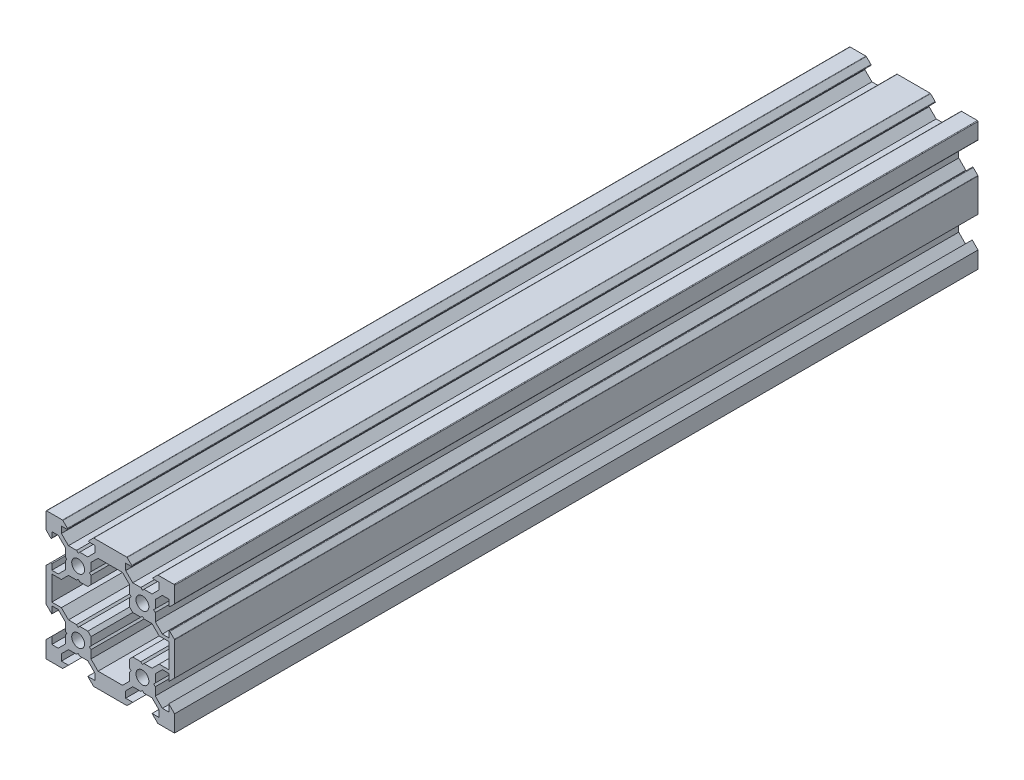
SolidWorks part; units mm, degrees
ref_plane "Front Plane" through (0, 0, 0) normal (0, 0, 1) x (1, 0, 0)
ref_plane "Top Plane" through (0, 0, 0) normal (0, 1, 0) x (1, 0, 0)
ref_plane "Right Plane" through (0, 0, 0) normal (1, 0, 0) x (0, 0, -1)
sketch "Sketch2" plane through (0, 0, 0) normal (0, 0, 1) x (1, 0, 0)
  line L160 (-6.22, 13.1326) -> (-4.02, 15.3326)
  line L161 (-4.02, 15.3326) -> (3.58, 15.3326)
  line L162 (3.58, 15.3326) -> (5.78, 13.1326)
  line L163 (5.78, 13.1326) -> (5.78, 10.6226)
  line L164 (5.78, 10.6226) -> (6.28, 10.1226)
  line L165 (6.28, 10.1226) -> (5.78, 9.6226)
  line L166 (5.78, 9.6226) -> (5.78, 7.1125)
  line L167 (5.78, 7.1125) -> (6.77, 6.1226)
  line L168 (6.77, 6.1226) -> (9.28, 6.1226)
  line L169 (9.28, 6.1226) -> (9.78, 6.6226)
  line L170 (9.78, 6.6226) -> (10.28, 6.1226)
  line L171 (10.28, 6.1226) -> (12.7901, 6.1226)
  line L172 (12.7901, 6.1226) -> (14.9901, 3.9226)
  line L173 (14.9901, 3.9226) -> (17.98, 3.9226)
  line L174 (17.98, 3.9226) -> (17.98, -3.6774)
  line L175 (17.98, -3.6774) -> (14.9901, -3.6774)
  line L176 (14.9901, -3.6774) -> (12.7901, -5.8774)
  line L177 (12.7901, -5.8774) -> (10.28, -5.8774)
  line L178 (9.78, -6.3774) -> (10.28, -5.8774)
  line L179 (9.28, -5.8774) -> (9.78, -6.3774)
  line L180 (9.28, -5.8774) -> (6.77, -5.8774)
  line L181 (6.77, -5.8774) -> (5.78, -6.8674)
  line L182 (5.78, -6.8674) -> (5.78, -9.3774)
  line L183 (6.28, -9.8774) -> (5.78, -9.3774)
  line L184 (5.78, -10.3774) -> (6.28, -9.8774)
  line L185 (5.78, -10.3774) -> (5.78, -12.8875)
  line L186 (5.78, -12.8875) -> (3.58, -15.0875)
  line L187 (3.58, -15.0875) -> (-4.02, -15.0875)
  line L188 (-4.02, -15.0875) -> (-6.22, -12.8875)
  line L189 (-6.22, -12.8875) -> (-6.22, -10.3774)
  line L190 (-6.72, -9.8774) -> (-6.22, -10.3774)
  line L191 (-6.22, -9.3774) -> (-6.72, -9.8774)
  line L192 (-6.22, -9.3774) -> (-6.22, -6.8674)
  line L193 (-6.22, -6.8674) -> (-7.2099, -5.8774)
  line L194 (-7.2099, -5.8774) -> (-9.72, -5.8774)
  line L195 (-10.22, -6.3774) -> (-9.72, -5.8774)
  line L196 (-10.72, -5.8774) -> (-10.22, -6.3774)
  line L197 (-10.72, -5.8774) -> (-13.23, -5.8774)
  line L198 (-13.23, -5.8774) -> (-15.43, -3.6774)
  line L199 (-15.43, -3.6774) -> (-18.42, -3.6774)
  line L200 (-18.42, -3.6774) -> (-18.42, 3.9226)
  line L201 (-18.42, 3.9226) -> (-15.43, 3.9226)
  line L202 (-15.43, 3.9226) -> (-13.23, 6.1226)
  line L203 (-13.23, 6.1226) -> (-10.72, 6.1226)
  line L204 (-10.72, 6.1226) -> (-10.22, 6.6226)
  line L205 (-10.22, 6.6226) -> (-9.72, 6.1226)
  line L206 (-9.72, 6.1226) -> (-7.2099, 6.1226)
  line L207 (-7.2099, 6.1226) -> (-6.22, 7.1125)
  line L208 (-6.22, 9.6226) -> (-6.72, 10.1226)
  line L209 (-6.72, 10.1226) -> (-6.22, 10.6226)
  line L210 (-6.22, 7.1125) -> (-6.22, 9.6226)
  line L211 (-6.22, 10.6226) -> (-6.22, 13.1326)
  line L212 (-5.0099, -16.0774) -> (-5.0099, -18.0774)
  line L213 (-5.0099, -18.0774) -> (-7.22, -18.0774)
  line L214 (-7.22, -18.0774) -> (-5.42, -19.8774)
  line L215 (-5.42, -19.8774) -> (4.98, -19.8774)
  line L216 (4.98, -19.8774) -> (6.78, -18.0774)
  line L217 (6.78, -18.0774) -> (4.57, -18.0774)
  line L218 (4.57, -18.0774) -> (4.57, -16.0774)
  line L219 (4.57, -16.0774) -> (6.77, -13.8774)
  line L220 (6.77, -13.8774) -> (9.28, -13.8774)
  line L221 (9.28, -13.8774) -> (9.78, -13.3774)
  line L222 (9.78, -13.3774) -> (10.28, -13.8774)
  line L223 (10.28, -13.8774) -> (12.7901, -13.8774)
  line L224 (12.7901, -13.8774) -> (14.9901, -16.0774)
  line L225 (14.9901, -16.0774) -> (14.9901, -18.0774)
  line L226 (14.9901, -18.0774) -> (12.78, -18.0774)
  line L227 (12.78, -18.0774) -> (14.58, -19.8774)
  line L228 (14.58, -19.8774) -> (19.78, -19.8774)
  line L229 (19.78, -19.8774) -> (19.78, -14.6774)
  line L230 (19.78, -14.6774) -> (17.98, -12.8774)
  line L231 (17.98, -12.8774) -> (17.98, -15.0875)
  line L232 (17.98, -15.0875) -> (15.98, -15.0875)
  line L233 (15.98, -15.0875) -> (13.78, -12.8875)
  line L234 (13.78, -12.8875) -> (13.78, -10.3774)
  line L235 (13.78, -10.3774) -> (13.28, -9.8774)
  line L236 (13.28, -9.8774) -> (13.78, -9.3774)
  line L237 (13.78, -9.3774) -> (13.78, -6.8674)
  line L238 (13.78, -6.8674) -> (15.98, -4.6674)
  line L239 (15.98, -4.6674) -> (17.98, -4.6674)
  line L240 (17.98, -4.6674) -> (17.98, -6.8774)
  line L241 (17.98, -6.8774) -> (19.78, -5.0774)
  line L242 (19.78, -5.0774) -> (19.78, 5.2397)
  line L243 (19.7215, 5.3812) -> (18.3215, 6.7812)
  line L244 (17.98, 6.6397) -> (17.98, 4.9125)
  line L245 (17.98, 4.9125) -> (15.98, 4.9125)
  line L246 (15.98, 4.9125) -> (13.78, 7.1125)
  line L247 (13.78, 7.1125) -> (13.78, 9.6226)
  line L248 (13.78, 9.6226) -> (13.28, 10.1226)
  line L249 (13.28, 10.1226) -> (13.78, 10.6226)
  line L250 (13.78, 10.6226) -> (13.78, 13.1326)
  line L251 (13.78, 13.1326) -> (15.98, 15.3326)
  line L252 (15.98, 15.3326) -> (17.98, 15.3326)
  line L253 (17.98, 15.3326) -> (17.98, 13.6054)
  line L254 (18.3215, 13.464) -> (19.7215, 14.864)
  line L255 (19.78, 15.0054) -> (19.78, 19.9226)
  line L256 (19.58, 20.1226) -> (14.6629, 20.1226)
  line L257 (14.5215, 20.064) -> (13.1215, 18.664)
  line L258 (13.2629, 18.3226) -> (14.9901, 18.3226)
  line L259 (14.9901, 18.3226) -> (14.9901, 16.3226)
  line L260 (14.9901, 16.3226) -> (12.7901, 14.1226)
  line L261 (12.7901, 14.1226) -> (10.28, 14.1226)
  line L262 (10.28, 14.1226) -> (9.78, 13.6226)
  line L263 (9.78, 13.6226) -> (9.28, 14.1226)
  line L264 (9.28, 14.1226) -> (6.77, 14.1226)
  line L265 (6.77, 14.1226) -> (4.57, 16.3226)
  line L266 (4.57, 16.3226) -> (4.57, 18.3226)
  line L267 (4.57, 18.3226) -> (6.2972, 18.3226)
  line L268 (6.4386, 18.664) -> (5.0386, 20.064)
  line L269 (4.8972, 20.1226) -> (-5.3371, 20.1226)
  line L270 (-5.4785, 20.064) -> (-6.8785, 18.664)
  line L271 (-6.7371, 18.3226) -> (-5.0099, 18.3226)
  line L272 (-5.0099, 18.3226) -> (-5.0099, 16.3226)
  line L273 (-5.0099, 16.3226) -> (-7.2099, 14.1226)
  line L274 (-7.2099, 14.1226) -> (-9.72, 14.1226)
  line L275 (-9.72, 14.1226) -> (-10.22, 13.6226)
  line L276 (-10.22, 13.6226) -> (-10.72, 14.1226)
  line L277 (-10.72, 14.1226) -> (-13.23, 14.1226)
  line L278 (-13.23, 14.1226) -> (-15.43, 16.3226)
  line L279 (-15.43, 16.3226) -> (-15.43, 18.3226)
  line L280 (-15.43, 18.3226) -> (-13.7028, 18.3226)
  line L281 (-13.5614, 18.664) -> (-14.9614, 20.064)
  line L282 (-15.1028, 20.1226) -> (-20.02, 20.1226)
  line L283 (-20.22, 19.9226) -> (-20.22, 15.0054)
  line L284 (-20.1614, 14.864) -> (-18.7614, 13.464)
  line L285 (-18.42, 13.6054) -> (-18.42, 15.3326)
  line L286 (-18.42, 15.3326) -> (-16.42, 15.3326)
  line L287 (-16.42, 15.3326) -> (-14.22, 13.1326)
  line L288 (-14.22, 13.1326) -> (-14.22, 10.6226)
  line L289 (-14.22, 10.6226) -> (-13.72, 10.1226)
  line L290 (-13.72, 10.1226) -> (-14.22, 9.6226)
  line L291 (-14.22, 9.6226) -> (-14.22, 7.1125)
  line L292 (-14.22, 7.1125) -> (-16.42, 4.9125)
  line L293 (-16.42, 4.9125) -> (-18.42, 4.9125)
  line L294 (-18.42, 4.9125) -> (-18.42, 6.6397)
  line L295 (-18.7614, 6.7812) -> (-20.1614, 5.3812)
  line L296 (-20.22, 5.2397) -> (-20.22, -5.0774)
  line L297 (-20.22, -5.0774) -> (-18.42, -6.8774)
  line L298 (-18.42, -6.8774) -> (-18.42, -4.6674)
  line L299 (-18.42, -4.6674) -> (-16.42, -4.6674)
  line L300 (-16.42, -4.6674) -> (-14.22, -6.8674)
  line L301 (-14.22, -6.8674) -> (-14.22, -9.3774)
  line L302 (-14.22, -9.3774) -> (-13.72, -9.8774)
  line L303 (-13.72, -9.8774) -> (-14.22, -10.3774)
  line L304 (-14.22, -10.3774) -> (-14.22, -12.8875)
  line L305 (-14.22, -12.8875) -> (-16.42, -15.0875)
  line L306 (-16.42, -15.0875) -> (-18.42, -15.0875)
  line L307 (-18.42, -15.0875) -> (-18.42, -12.8774)
  line L308 (-18.42, -12.8774) -> (-20.22, -14.6774)
  line L309 (-20.22, -14.6774) -> (-20.22, -19.8774)
  line L310 (-20.22, -19.8774) -> (-15.02, -19.8774)
  line L311 (-15.02, -19.8774) -> (-13.22, -18.0774)
  line L312 (-13.22, -18.0774) -> (-15.43, -18.0774)
  line L313 (-15.43, -18.0774) -> (-15.43, -16.0774)
  line L314 (-15.43, -16.0774) -> (-13.23, -13.8774)
  line L315 (-13.23, -13.8774) -> (-10.72, -13.8774)
  line L316 (-10.72, -13.8774) -> (-10.22, -13.3774)
  line L317 (-10.22, -13.3774) -> (-9.72, -13.8774)
  line L318 (-9.72, -13.8774) -> (-7.2099, -13.8774)
  line L319 (-7.2099, -13.8774) -> (-5.0099, -16.0774)
  line L320 (-13.72, 10.1226) -> (-6.72, 10.1226) construction
  line L321 (6.28, 10.1226) -> (13.28, 10.1226) construction
  line L322 (-13.72, -9.8774) -> (-6.72, -9.8774) construction
  line L323 (6.28, -9.8774) -> (13.28, -9.8774) construction
  arc A22 (19.78, 5.2397) -> (19.7215, 5.3812) centre (19.58, 5.2397) ccw
  arc A23 (18.3215, 6.7812) -> (17.98, 6.6397) centre (18.18, 6.6397) ccw
  arc A24 (17.98, 13.6054) -> (18.3215, 13.464) centre (18.18, 13.6054) ccw
  arc A25 (19.7215, 14.864) -> (19.78, 15.0054) centre (19.58, 15.0054) ccw
  arc A26 (19.78, 19.9226) -> (19.58, 20.1226) centre (19.58, 19.9226) ccw
  arc A27 (14.6629, 20.1226) -> (14.5215, 20.064) centre (14.6629, 19.9226) ccw
  arc A28 (13.1215, 18.664) -> (13.2629, 18.3226) centre (13.2629, 18.5226) ccw
  arc A29 (6.2972, 18.3226) -> (6.4386, 18.664) centre (6.2972, 18.5226) ccw
  arc A30 (5.0386, 20.064) -> (4.8972, 20.1226) centre (4.8972, 19.9226) ccw
  arc A31 (-5.3371, 20.1226) -> (-5.4785, 20.064) centre (-5.3371, 19.9226) ccw
  arc A32 (-6.8785, 18.664) -> (-6.7371, 18.3226) centre (-6.7371, 18.5226) ccw
  arc A33 (-13.7028, 18.3226) -> (-13.5614, 18.664) centre (-13.7028, 18.5226) ccw
  arc A34 (-14.9614, 20.064) -> (-15.1028, 20.1226) centre (-15.1028, 19.9226) ccw
  arc A35 (-20.02, 20.1226) -> (-20.22, 19.9226) centre (-20.02, 19.9226) ccw
  arc A36 (-20.22, 15.0054) -> (-20.1614, 14.864) centre (-20.02, 15.0054) ccw
  arc A37 (-18.7614, 13.464) -> (-18.42, 13.6054) centre (-18.62, 13.6054) ccw
  arc A38 (-18.42, 6.6397) -> (-18.7614, 6.7812) centre (-18.62, 6.6397) ccw
  arc A39 (-20.1614, 5.3812) -> (-20.22, 5.2397) centre (-20.02, 5.2397) ccw
  circle A40 centre (-10.22, 10.1226) radius 2
  circle A41 centre (9.78, 10.1226) radius 2
  circle A42 centre (-10.22, -9.8774) radius 2
  circle A43 centre (9.78, -9.8774) radius 2
  dimension "D1" = 4
extrude "Boss-Extrude1" add sketch "Sketch2" against normal blind 250
